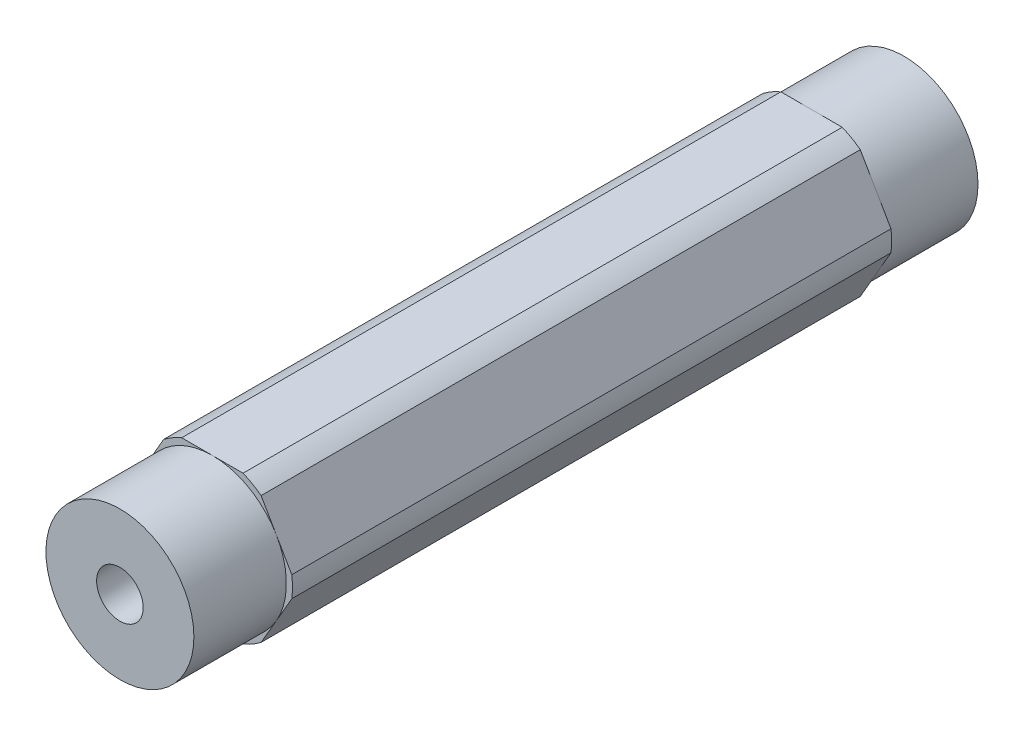
SolidWorks part; units mm, degrees
material "6061-T6 (SS)"
ref_plane "Front Plane" through (0, 0, 0) normal (0, 0, 1) x (1, 0, 0)
ref_plane "Top Plane" through (0, 0, 0) normal (0, 1, 0) x (1, 0, 0)
ref_plane "Right Plane" through (0, 0, 0) normal (1, 0, 0) x (0, 0, -1)
sketch "Sketch1" plane through (0, 0, 0) normal (0, 0, 1) x (1, 0, 0)
  line L1 (3.6662, 6.35) -> (-3.6662, 6.35)
  line L2 (-3.6662, 6.35) -> (-7.3323, 0)
  line L3 (-7.3323, 0) -> (-3.6662, -6.35)
  line L4 (-3.6662, -6.35) -> (3.6662, -6.35)
  line L5 (3.6662, -6.35) -> (7.3323, 0)
  line L6 (7.3323, 0) -> (3.6662, 6.35)
  circle A0 centre (0, 0) radius 6.35 construction
  circle A1 centre (0, 0) radius 2
  circle A2 centre (0, 0) radius 6.875
  point P1 (0, 6.35)
  dimension "D2" = 13.75
  dimension "D3" = 4
  dimension "D1" = 12.7
extrude "Boss-Extrude1" add sketch "Sketch1" along normal mid plane 51.435 contours L6 A2 L1 L2 L3 L4 L5 A1
sketch "Sketch4" plane through (0, 0, 25.7175) normal (0, 0, 1) x (1, 0, 0)
  circle A0 centre (0, 0) radius 6.35
  circle A1 centre (0, 0) radius 2 construction
  circle A2 centre (0, 0) radius 2
  dimension "D1" = 12.7
extrude "Boss-Extrude2" add sketch "Sketch4" along normal blind 7.9375
mirror "Mirror1" about plane through (0, 0, 0) normal (0, 0, 1) of "Boss-Extrude2"
equation "\"D2@Sketch1\"=13.75mm"
equation "\"D3@Sketch1\"=4mm"
